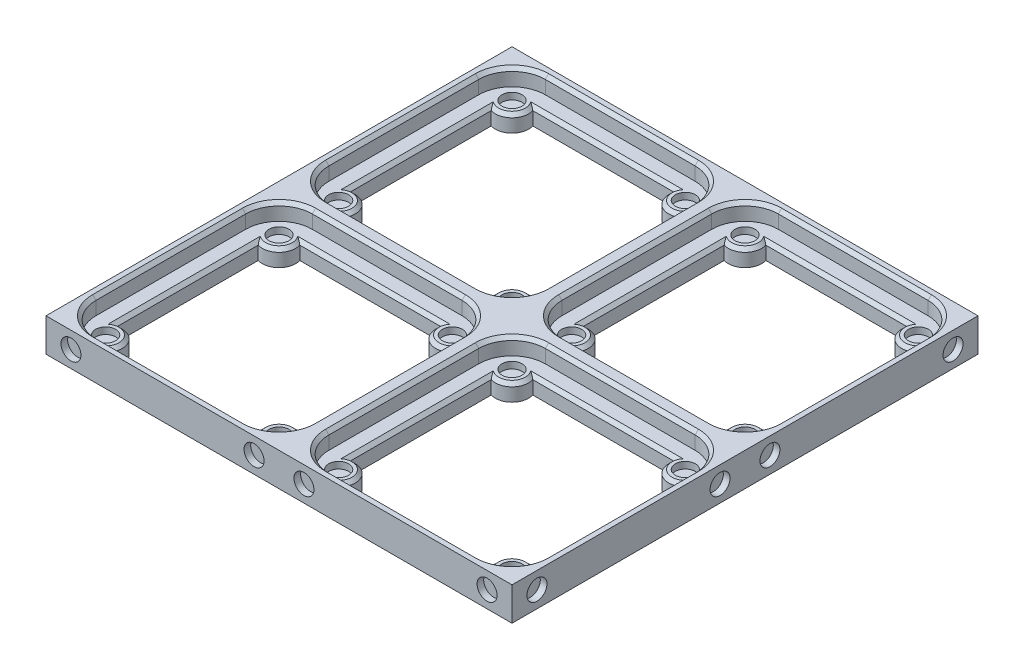
SolidWorks part; units mm, degrees
ref_plane "Front Plane" through (0, 0, 0) normal (0, 0, 1) x (1, 0, 0)
ref_plane "Top Plane" through (0, 0, 0) normal (0, 1, 0) x (1, 0, 0)
ref_plane "Right Plane" through (0, 0, 0) normal (1, 0, 0) x (0, 0, -1)
sketch "Sketch1" plane through (0, 0, 0) normal (0, 1, 0) x (1, 0, 0)
  line L1 (0, 0) -> (70, 0)
  line L2 (0, 0) -> (0, 70)
  line L3 (0, 70) -> (70, 70)
  line L4 (70, 0) -> (70, 70)
  dimension "D1" = 70
  dimension "D2" = 70
extrude "Boss-Extrude2" add sketch "Sketch1" along normal blind 7
sketch "Sketch3" plane through (0, 7, 0) normal (0, 1, 0) x (1, 0, 0)
  line L8 (2.5, 67.5) -> (2.5, 2.5)
  line L9 (2.5, 2.5) -> (67.5, 2.5)
  line L10 (67.5, 2.5) -> (67.5, 67.5)
  line L11 (67.5, 67.5) -> (2.5, 67.5)
  line L12 (2.5, 57.5) -> (2.5, 12.5)
  line L13 (12.5, 2.5) -> (57.5, 2.5)
  line L14 (67.5, 12.5) -> (67.5, 57.5)
  line L15 (57.5, 67.5) -> (12.5, 67.5)
  arc A0 (2.5, 12.5) -> (12.5, 2.5) centre (12.5, 12.5) ccw
  arc A1 (57.5, 2.5) -> (67.5, 12.5) centre (57.5, 12.5) ccw
  arc A2 (67.5, 57.5) -> (57.5, 67.5) centre (57.5, 57.5) ccw
  arc A3 (2.5, 57.5) -> (12.5, 67.5) centre (12.5, 57.5) cw
  dimension "D2" = 10
  dimension "D1" = 2.5
extrude "Cut-Extrude1" cut sketch "Sketch3" against normal blind 5
sketch "Sketch9" plane through (0, 0, 0) normal (0, -1, 0) x (1, 0, 0)
  line L1 (0, -70) -> (70, -70)
  line L2 (0, -70) -> (0, 0)
  line L3 (0, 0) -> (70, 0)
  line L4 (70, -70) -> (70, 0)
extrude "Boss-Extrude3" add sketch "Sketch9" along normal blind 5
sketch "Sketch20" plane through (0, 2, 0) normal (0, 1, 0) x (1, 0, 0)
  line L0 (35, 35) -> (8.9645, 61.0355) construction
  line L19 (12.5, 7.5) -> (57.5, 7.5)
  line L20 (62.5, 12.5) -> (62.5, 57.5)
  line L21 (57.5, 62.5) -> (12.5, 62.5)
  line L22 (7.5, 57.5) -> (7.5, 12.5)
  line L23 (13.7452, 7.5) -> (56.2548, 7.5)
  line L24 (62.5, 13.7452) -> (62.5, 56.2548)
  line L25 (56.2548, 62.5) -> (13.7452, 62.5)
  line L26 (7.5, 56.2548) -> (7.5, 13.7452)
  arc A0 (56.2548, 62.5) -> (62.5, 56.2548) centre (61.0355, 61.0355) ccw
  arc A1 (62.5, 13.7452) -> (56.2548, 7.5) centre (61.0355, 8.9645) ccw
  arc A2 (13.7452, 7.5) -> (7.5, 13.7452) centre (8.9645, 8.9645) ccw
  circle A4 centre (8.9645, 61.0355) radius 3
  circle A5 centre (8.9645, 8.9645) radius 3
  circle A6 centre (61.0355, 8.9645) radius 3
  circle A7 centre (61.0355, 61.0355) radius 3
  arc A21 (7.5, 56.2548) -> (13.7452, 62.5) centre (8.9645, 61.0355) ccw
  arc A24 (7.5, 12.5) -> (12.5, 7.5) centre (12.5, 12.5) ccw
  arc A25 (57.5, 7.5) -> (62.5, 12.5) centre (57.5, 12.5) ccw
  arc A26 (62.5, 57.5) -> (57.5, 62.5) centre (57.5, 57.5) ccw
  arc A27 (12.5, 62.5) -> (7.5, 57.5) centre (12.5, 57.5) ccw
  point P8 (35, 35)
  dimension "D2" = 6
  dimension "D3" = 4
  dimension "D4" = 36.8198
  dimension "D1" = 5
extrude "Cut-Extrude11" cut sketch "Sketch20" against normal through all contours L23 A1 L24 A0 L25 A21 L26 A2
sketch "Sketch21" plane through (0, 2, 0) normal (0, 1, 0) x (1, 0, 0)
  circle A0 centre (8.9645, 61.0355) radius 3
  circle A1 centre (61.0355, 61.0355) radius 3
  circle A2 centre (61.0355, 8.9645) radius 3
  circle A3 centre (8.9645, 8.9645) radius 3
extrude "Cut-Extrude12" cut sketch "Sketch21" against normal blind 2 contours A0 | A1 | A2 | A3
chamfer "Chamfer3" distance 1 angle 45 16 edges at (35, 7, -2.5) (64.5711, 7, -5.4289) (5.4289, 7, -5.4289) (67.5, 7, -35) (2.5, 7, -35) (64.5711, 7, -64.5711) (5.4289, 7, -64.5711) (35, 7, -67.5) (12.5, 2, -12.5) (35, 2, -7.5) (57.5, 2, -12.5) (62.5, 2, -35) (57.5, 2, -57.5) (7.5, 2, -35) (12.5, 2, -57.5) (35, 2, -62.5)
sketch "Sketch22" plane through (0, -5, 0) normal (0, -1, 0) x (1, 0, 0)
  line L0 (7.5, -13.7452) -> (7.5, -56.2548)
  line L1 (0, 0) -> (70, 0)
  line L2 (0, 0) -> (0, -70)
  line L3 (0, -70) -> (70, -70)
  line L4 (70, 0) -> (70, -70)
  line L6 (13.7452, -62.5) -> (56.2548, -62.5)
  line L8 (62.5, -56.2548) -> (62.5, -13.7452)
  line L10 (56.2548, -7.5) -> (13.7452, -7.5)
  arc A0 (7.5, -13.7452) -> (13.7452, -7.5) centre (8.9645, -8.9645) ccw
  arc A1 (56.2548, -7.5) -> (62.5, -13.7452) centre (61.0355, -8.9645) ccw
  arc A2 (62.5, -56.2548) -> (56.2548, -62.5) centre (61.0355, -61.0355) ccw
  arc A3 (13.7452, -62.5) -> (7.5, -56.2548) centre (8.9645, -61.0355) ccw
extrude "Cut-Extrude13" cut sketch "Sketch22" against normal blind 2
ref_plane "Plane2" through (0, 0, -35) normal (0, 0, 1) x (1, 0, 0)
ref_plane "Plane3" through (35, 0, 0) normal (-1, 0, 0) x (0, 0, 1)
sketch "Sketch27" plane through (0, 0, 0) normal (-1, 0, 0) x (0, 0, 1)
  line L0 (-70, -3) -> (-70, 7)
  line L1 (-70, 7) -> (-70, 2)
  line L2 (-70, 2) -> (-62.5, 2)
  line L3 (-35, -5.5) -> (-35, 5.5) construction
  circle A0 centre (-62.5, 2) radius 3
  circle A1 centre (-7.5, 2) radius 3
extrude "Cut-Extrude27" cut sketch "Sketch27" against normal blind 2
sketch "Sketch28" plane through (0, 0, 0) normal (0, 0, 1) x (1, 0, 0)
  line L0 (0, -3) -> (0, 7)
  line L1 (0, 7) -> (0, 2)
  line L2 (0, 2) -> (7.5, 2)
  line L3 (35, 5.5) -> (35, -5.5) construction
  circle A0 centre (7.5, 2) radius 3
  circle A1 centre (62.5, 2) radius 3
extrude "Cut-Extrude28" cut sketch "Sketch28" against normal blind 2
mirror "Mirror2" about plane through (0, 7, -70) normal (0, 0, 1) of bodies 126
mirror "Mirror3" about plane through (70, 7, 0) normal (-1, 0, 0) of bodies 130
